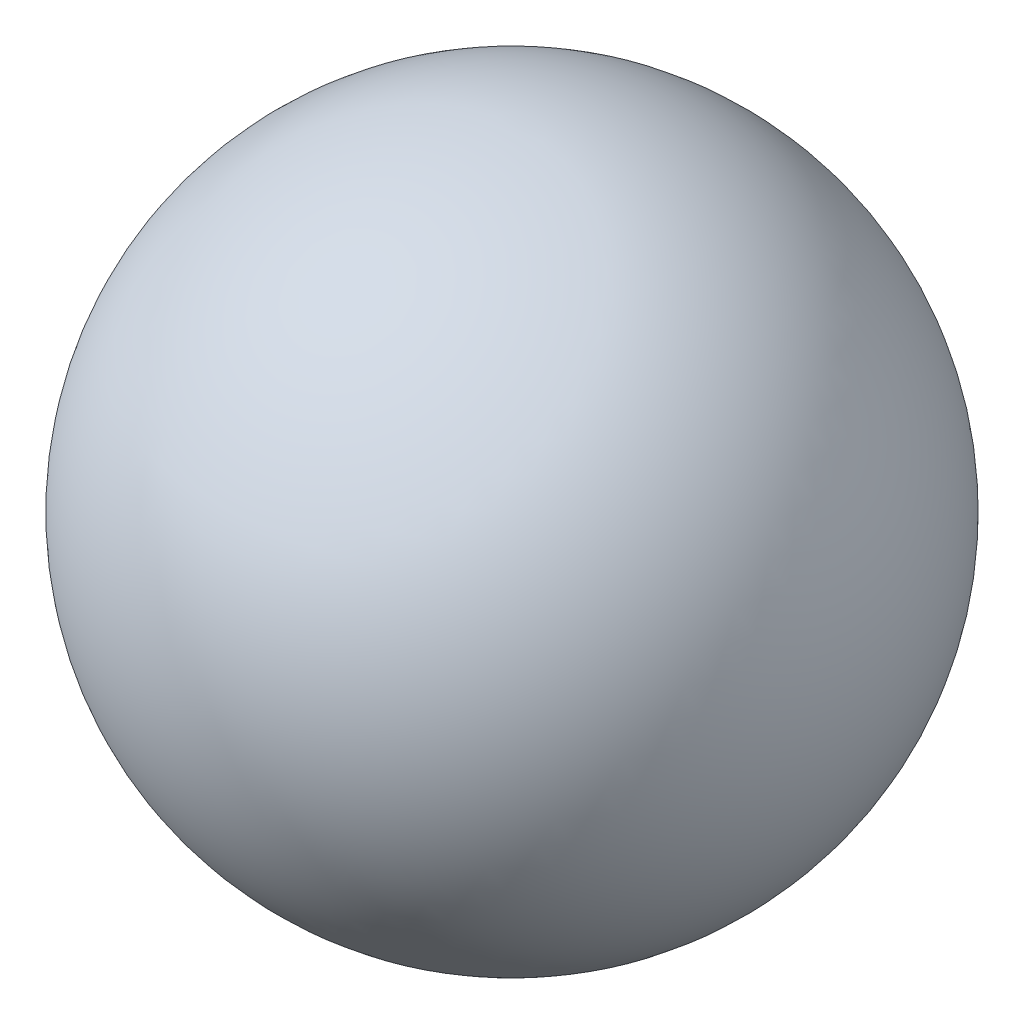
SolidWorks part; units mm, degrees
ref_plane "Front Plane" through (0, 0, 0) normal (0, 0, 1) x (1, 0, 0)
ref_plane "Top Plane" through (0, 0, 0) normal (0, 1, 0) x (1, 0, 0)
ref_plane "Right Plane" through (0, 0, 0) normal (1, 0, 0) x (0, 0, -1)
sketch "Sketch1" plane through (0, 0, 0) normal (0, 0, 1) x (1, 0, 0)
  line L0 (0, -11.25) -> (0, 11.25)
  arc A0 (0, 11.25) -> (0, -11.25) centre (0, 0) ccw
  dimension "D1" = 22.5
revolve "Revolve4" add sketch "Sketch1" angle 360 about L0
